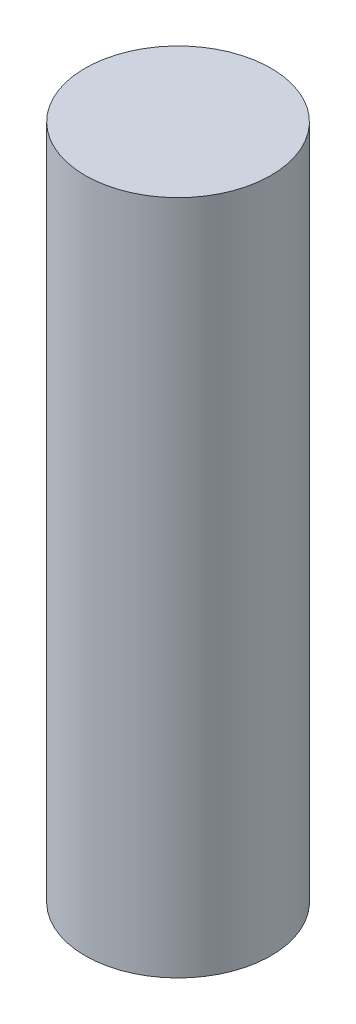
SolidWorks part; units mm, degrees
ref_plane "Front Plane" through (0, 0, 0) normal (0, 0, 1) x (1, 0, 0)
ref_plane "Top Plane" through (0, 0, 0) normal (0, 1, 0) x (1, 0, 0)
ref_plane "Right Plane" through (0, 0, 0) normal (1, 0, 0) x (0, 0, -1)
sketch "Sketch1" plane through (0, 0, 0) normal (0, 1, 0) x (1, 0, 0)
  circle A0 centre (0, 0) radius 13.75
extrude "Boss-Extrude1" add sketch "Sketch1" along normal blind 100
